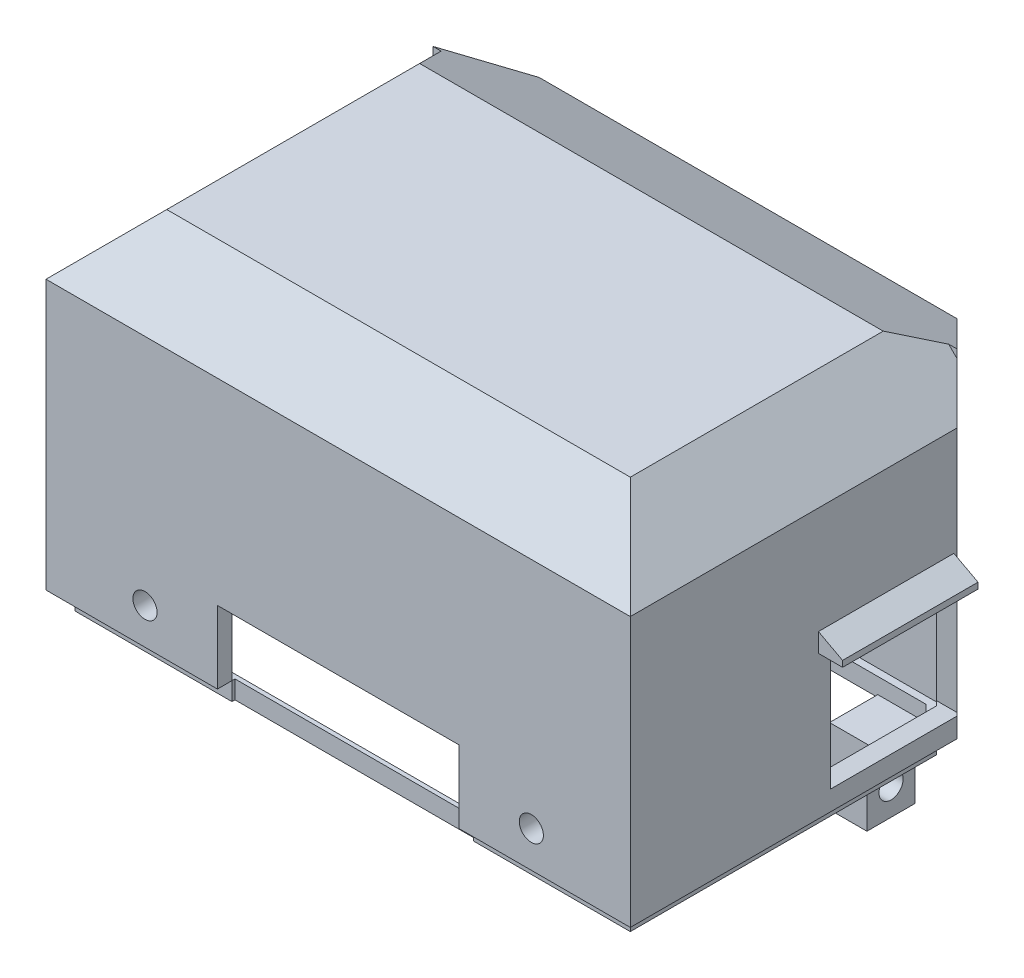
SolidWorks part; units mm, degrees
ref_plane "Front Plane" through (0, 0, 0) normal (0, 0, 1) x (1, 0, 0)
ref_plane "Top Plane" through (0, 0, 0) normal (0, 1, 0) x (1, 0, 0)
ref_plane "Right Plane" through (0, 0, 0) normal (1, 0, 0) x (0, 0, -1)
ref_plane "PXm48_4" through (-48.4, 0, 0) normal (1, 0, 0) x (0, 0, -1)
sketch "Sketch1" plane through (-48.4, 0, 0) normal (1, 0, 0) x (0, 0, -1)
  line L0 (-11.9, -4) -> (48.2, -4)
  line L1 (48.2, -4) -> (48.2, 46.4488)
  line L2 (48.2, 46.4488) -> (40, 50.6)
  line L3 (40, 50.6) -> (-1.9, 50.6)
  line L4 (-1.9, 50.6) -> (-11.9, 40.6)
  line L5 (-11.9, 40.6) -> (-11.9, -4)
extrude "Head Block" add sketch "Sketch1" along normal blind 96.8
sketch "Sketch2" plane through (0, 0, 0) normal (0, 0, 1) x (1, 0, 0)
  line L0 (-37.4, 51.6) -> (-49.4, 51.6)
  line L1 (-49.4, 51.6) -> (-49.4, 39.6)
  line L2 (-49.4, 39.6) -> (-37.4, 51.6)
extrude "Roof Corner Facet L" cut sketch "Sketch2" against normal through all and the other way through all
sketch "Sketch3" plane through (0, 0, 0) normal (0, 0, 1) x (1, 0, 0)
  line L0 (37.4, 51.6) -> (49.4, 51.6)
  line L1 (49.4, 51.6) -> (49.4, 39.6)
  line L2 (49.4, 39.6) -> (37.4, 51.6)
extrude "Roof Corner Facet R" cut sketch "Sketch3" against normal through all and the other way through all
sketch "Sketch4" plane through (0, 0, 0) normal (0, 1, 0) x (1, 0, 0)
  line L0 (-30.4, 60.2) -> (-49.4, 60.2)
  line L1 (-49.4, 60.2) -> (-49.4, 41.2)
  line L2 (-49.4, 41.2) -> (-30.4, 60.2)
extrude "Front Corner Facet L" cut sketch "Sketch4" against normal through all and the other way through all
sketch "Sketch5" plane through (0, 0, 0) normal (0, 1, 0) x (1, 0, 0)
  line L0 (30.4, 60.2) -> (49.4, 60.2)
  line L1 (49.4, 60.2) -> (49.4, 41.2)
  line L2 (49.4, 41.2) -> (30.4, 60.2)
extrude "Front Corner Facet R" cut sketch "Sketch5" against normal through all and the other way through all
shell "Shell" thickness 2.4
ref_plane "PXm47_9" through (-47.9, 0, 0) normal (1, 0, 0) x (0, 0, -1)
sketch "Sketch6" plane through (-47.9, 0, 0) normal (1, 0, 0) x (0, 0, -1)
  line L0 (47.2, 40) -> (56, 40)
  line L1 (56, 40) -> (56, 42.5)
  line L2 (56, 42.5) -> (47.2, 46.955)
  line L3 (47.2, 46.955) -> (47.2, 40)
extrude "Brow" add sketch "Sketch6" along normal blind 95.8
sketch "Sketch7" plane through (0, 0, 0) normal (0, 1, 0) x (1, 0, 0)
  line L0 (-30.4, 60.2) -> (-49.4, 60.2)
  line L1 (-49.4, 60.2) -> (-49.4, 41.2)
  line L2 (-49.4, 41.2) -> (-30.4, 60.2)
extrude "Brow Corner Facet L" cut sketch "Sketch7" against normal through all and the other way through all
sketch "Sketch8" plane through (0, 0, 0) normal (0, 1, 0) x (1, 0, 0)
  line L0 (30.4, 60.2) -> (49.4, 60.2)
  line L1 (49.4, 60.2) -> (49.4, 41.2)
  line L2 (49.4, 41.2) -> (30.4, 60.2)
extrude "Brow Corner Facet R" cut sketch "Sketch8" against normal through all and the other way through all
ref_plane "PYm54_5" through (0, 0, -54.5) normal (0, 0, 1) x (1, 0, 0)
sketch "Sketch9" plane through (0, 0, -54.5) normal (0, 0, 1) x (1, 0, 0)
  line L0 (-46.4, 39.99) -> (46.4, 39.99)
  line L1 (46.4, 39.99) -> (46.4, 40.8)
  line L2 (46.4, 40.8) -> (-46.4, 40.8)
  line L3 (-46.4, 40.8) -> (-46.4, 39.99)
extrude "Brow Drip Groove" cut sketch "Sketch9" along normal blind 1
ref_plane "PZm7" through (0, -7, 0) normal (0, 1, 0) x (1, 0, 0)
sketch "Sketch10" plane through (0, -7, 0) normal (0, 1, 0) x (1, 0, 0)
  line L0 (-46, -9.5) -> (46, -9.5)
  line L1 (46, -9.5) -> (46, 41.2059)
  line L2 (46, 41.2059) -> (41.4059, 45.8)
  line L3 (41.4059, 45.8) -> (-41.4059, 45.8)
  line L4 (-41.4059, 45.8) -> (-46, 41.2059)
  line L5 (-46, 41.2059) -> (-46, -9.5)
  line L6 (-44.8, -8.3) -> (44.8, -8.3)
  line L7 (44.8, -8.3) -> (44.8, 40.7088)
  line L8 (44.8, 40.7088) -> (40.9088, 44.6)
  line L9 (40.9088, 44.6) -> (-40.9088, 44.6)
  line L10 (-40.9088, 44.6) -> (-44.8, 40.7088)
  line L11 (-44.8, 40.7088) -> (-44.8, -8.3)
extrude "Seam Skirt" add sketch "Sketch10" along normal blind 3.01
ref_plane "PZm12_5" through (0, -12.5, 0) normal (0, 1, 0) x (1, 0, 0)
sketch "Sketch11" plane through (0, -12.5, 0) normal (0, 1, 0) x (1, 0, 0)
  line L0 (-45.7, 30) -> (-39.5, 30)
  line L1 (-39.5, 30) -> (-39.5, 38)
  line L2 (-39.5, 38) -> (-45.7, 38)
  line L3 (-45.7, 38) -> (-45.7, 30)
extrude "Seam Block L" add sketch "Sketch11" along normal blind 8.5
ref_plane "PZm4_01" through (0, -4.01, 0) normal (0, 1, 0) x (1, 0, 0)
sketch "Sketch12" plane through (0, -4.01, 0) normal (0, 1, 0) x (1, 0, 0)
  line L0 (-46.2, 30) -> (-39.5, 30)
  line L1 (-39.5, 30) -> (-39.5, 38)
  line L2 (-39.5, 38) -> (-46.2, 38)
  line L3 (-46.2, 38) -> (-46.2, 30)
extrude "Seam Block Root L" add sketch "Sketch12" along normal blind 4.01
ref_plane "PXm45_8" through (-45.8, 0, 0) normal (1, 0, 0) x (0, 0, -1)
sketch "Sketch13" plane through (-45.8, 0, 0) normal (1, 0, 0) x (0, 0, -1)
  circle A0 centre (34, -8) radius 2
extrude "Seam Insert L" cut sketch "Sketch13" along normal blind 6.1
sketch "Sketch14" plane through (0, -12.5, 0) normal (0, 1, 0) x (1, 0, 0)
  line L0 (39.5, 30) -> (45.7, 30)
  line L1 (45.7, 30) -> (45.7, 38)
  line L2 (45.7, 38) -> (39.5, 38)
  line L3 (39.5, 38) -> (39.5, 30)
extrude "Seam Block R" add sketch "Sketch14" along normal blind 8.5
sketch "Sketch15" plane through (0, -4.01, 0) normal (0, 1, 0) x (1, 0, 0)
  line L0 (39.5, 30) -> (46.2, 30)
  line L1 (46.2, 30) -> (46.2, 38)
  line L2 (46.2, 38) -> (39.5, 38)
  line L3 (39.5, 38) -> (39.5, 30)
extrude "Seam Block Root R" add sketch "Sketch15" along normal blind 4.01
ref_plane "PX39_7" through (39.7, 0, 0) normal (1, 0, 0) x (0, 0, -1)
sketch "Sketch16" plane through (39.7, 0, 0) normal (1, 0, 0) x (0, 0, -1)
  circle A0 centre (34, -8) radius 2
extrude "Seam Insert R" cut sketch "Sketch16" along normal blind 6.1
ref_plane "PY9" through (0, 0, 9) normal (0, 0, 1) x (1, 0, 0)
sketch "Sketch17" plane through (0, 0, 9) normal (0, 0, 1) x (1, 0, 0)
  line L0 (-20, -8) -> (20, -8)
  line L1 (20, -8) -> (20, 8)
  line L2 (20, 8) -> (-20, 8)
  line L3 (-20, 8) -> (-20, -8)
extrude "Cable Window" cut sketch "Sketch17" along normal blind 3.9
ref_plane "PY3_5" through (0, 0, 3.5) normal (0, 0, 1) x (1, 0, 0)
sketch "Sketch18" plane through (0, 0, 3.5) normal (0, 0, 1) x (1, 0, 0)
  circle A0 centre (-32, 2) radius 4
  circle A1 centre (32, 2) radius 4
extrude "Flange Bosses" add sketch "Sketch18" along normal blind 6.2
ref_plane "PY5_4" through (0, 0, 5.4) normal (0, 0, 1) x (1, 0, 0)
sketch "Sketch19" plane through (0, 0, 5.4) normal (0, 0, 1) x (1, 0, 0)
  circle A0 centre (-32, 2) radius 2
  circle A1 centre (32, 2) radius 2
extrude "Flange Insert Holes" cut sketch "Sketch19" along normal blind 7
ref_plane "PZ17" through (0, 17, 0) normal (0, 1, 0) x (1, 0, 0)
sketch "Sketch20" plane through (0, 17, 0) normal (0, 1, 0) x (1, 0, 0)
  line L0 (-18.9, 29.3) -> (-14.9, 29.3)
  line L1 (-14.9, 29.3) -> (-14.9, 46.3)
  line L2 (-14.9, 46.3) -> (-18.9, 46.3)
  line L3 (-18.9, 46.3) -> (-18.9, 29.3)
extrude "Camera Rail L" add sketch "Sketch20" along normal blind 29
sketch "Sketch21" plane through (0, 17, 0) normal (0, 1, 0) x (1, 0, 0)
  line L0 (-15.4, 29.3) -> (-12.9, 29.3)
  line L1 (-12.9, 29.3) -> (-12.9, 30.35)
  line L2 (-12.9, 30.35) -> (-15.4, 30.35)
  line L3 (-15.4, 30.35) -> (-15.4, 29.3)
extrude "Camera Rear Lip L" add sketch "Sketch21" along normal blind 27.2
sketch "Sketch22" plane through (0, 17, 0) normal (0, 1, 0) x (1, 0, 0)
  line L0 (14.9, 29.3) -> (18.9, 29.3)
  line L1 (18.9, 29.3) -> (18.9, 46.3)
  line L2 (18.9, 46.3) -> (14.9, 46.3)
  line L3 (14.9, 46.3) -> (14.9, 29.3)
extrude "Camera Rail R" add sketch "Sketch22" along normal blind 29
sketch "Sketch23" plane through (0, 17, 0) normal (0, 1, 0) x (1, 0, 0)
  line L0 (12.9, 29.3) -> (15.4, 29.3)
  line L1 (15.4, 29.3) -> (15.4, 30.35)
  line L2 (15.4, 30.35) -> (12.9, 30.35)
  line L3 (12.9, 30.35) -> (12.9, 29.3)
extrude "Camera Rear Lip R" add sketch "Sketch23" along normal blind 27.2
ref_plane "PZ45_5" through (0, 45.5, 0) normal (0, 1, 0) x (1, 0, 0)
sketch "Sketch24" plane through (0, 45.5, 0) normal (0, 1, 0) x (1, 0, 0)
  line L0 (-18.9, 34) -> (18.9, 34)
  line L1 (18.9, 34) -> (18.9, 38)
  line L2 (18.9, 38) -> (-18.9, 38)
  line L3 (-18.9, 38) -> (-18.9, 34)
extrude "Camera Top Bar" add sketch "Sketch24" along normal blind 1.5
ref_plane "PZ16_5" through (0, 16.5, 0) normal (0, 1, 0) x (1, 0, 0)
sketch "Sketch25" plane through (0, 16.5, 0) normal (0, 1, 0) x (1, 0, 0)
  circle A0 centre (-16.9, 31) radius 0.8
  circle A1 centre (-16.9, 43.5) radius 0.8
  circle A2 centre (16.9, 31) radius 0.8
  circle A3 centre (16.9, 43.5) radius 0.8
extrude "Retainer Pilots" cut sketch "Sketch25" along normal blind 7.5
sketch "Sketch26" plane through (0, 0, 0) normal (0, 1, 0) x (1, 0, 0)
  line L0 (0, 33) -> (0, 43)
ref_plane "Plane15" through (0, 0, -43) normal (0, 0, -1) x (-1, 0, 0)
sketch "Sketch28" plane through (0, 0, -43) normal (0, 0, -1) x (-1, 0, 0)
  line L0 (4.8, 23.8) -> (-4.8, 23.8)
  line L1 (-4.8, 23.8) -> (-4.8, 33.4)
  line L2 (-4.8, 33.4) -> (4.8, 33.4)
  line L3 (4.8, 33.4) -> (4.8, 23.8)
extrude "Camera Window" cut sketch "Sketch28" along normal blind 6.7 draft 29.75 draft outward yes
sketch "Sketch29" plane through (0, 0, 0) normal (0, 1, 0) x (1, 0, 0)
  line L0 (-14.5, 32) -> (-24.5, 32)
ref_plane "Plane16" through (-24.5, 0, -32) normal (-1, 0, 0) x (0, 0, 1)
sketch "Sketch31" plane through (-24.5, 0, -32) normal (-1, 0, 0) x (0, 0, 1)
  line L0 (3.2, 6.8) -> (-3.2, 6.8)
  line L1 (-3.2, 6.8) -> (-3.2, 11.2)
  line L2 (-3.2, 11.2) -> (3.2, 11.2)
  line L3 (3.2, 11.2) -> (3.2, 6.8)
extrude "ToF Window Left" cut sketch "Sketch31" along normal blind 25.4 draft 17.5
sketch "Sketch32" plane through (0, 0, 0) normal (0, 1, 0) x (1, 0, 0)
  line L0 (0, 33) -> (0, 43)
ref_plane "Plane17" through (0, 0, -43) normal (0, 0, -1) x (-1, 0, 0)
sketch "Sketch34" plane through (0, 0, -43) normal (0, 0, -1) x (-1, 0, 0)
  line L0 (3.2, 6.8) -> (-3.2, 6.8)
  line L1 (-3.2, 6.8) -> (-3.2, 11.2)
  line L2 (-3.2, 11.2) -> (3.2, 11.2)
  line L3 (3.2, 11.2) -> (3.2, 6.8)
extrude "ToF Window Ahead" cut sketch "Sketch34" along normal blind 6.7 draft 17.5 draft outward yes
sketch "Sketch35" plane through (0, 0, 0) normal (0, 1, 0) x (1, 0, 0)
  line L0 (14.5, 32) -> (24.5, 32)
ref_plane "Plane18" through (24.5, 0, -32) normal (1, 0, 0) x (0, 0, -1)
sketch "Sketch37" plane through (24.5, 0, -32) normal (1, 0, 0) x (0, 0, -1)
  line L0 (3.2, 6.8) -> (-3.2, 6.8)
  line L1 (-3.2, 6.8) -> (-3.2, 11.2)
  line L2 (-3.2, 11.2) -> (3.2, 11.2)
  line L3 (3.2, 11.2) -> (3.2, 6.8)
extrude "ToF Window Right" cut sketch "Sketch37" along normal blind 25.4 draft 17.5
ref_plane "PXm13" through (-13, 0, 0) normal (1, 0, 0) x (0, 0, -1)
sketch "Sketch38" plane through (-13, 0, 0) normal (1, 0, 0) x (0, 0, -1)
  line L0 (47.7, 14) -> (54.2, 14)
  line L1 (54.2, 14) -> (54.2, 15)
  line L2 (54.2, 15) -> (47.7, 18.6)
  line L3 (47.7, 18.6) -> (47.7, 14)
extrude "ToF Hood Ahead" add sketch "Sketch38" along normal blind 26
ref_plane "PYm41_7" through (0, 0, -41.7) normal (0, 0, 1) x (1, 0, 0)
sketch "Sketch39" plane through (0, 0, -41.7) normal (0, 0, 1) x (1, 0, 0)
  line L0 (-47.9, 19.7356) -> (-52.4, 19.7356)
  line L1 (-52.4, 19.7356) -> (-52.4, 20.7356)
  line L2 (-52.4, 20.7356) -> (-47.9, 23.1356)
  line L3 (-47.9, 23.1356) -> (-47.9, 19.7356)
extrude "ToF Hood Left" add sketch "Sketch39" along normal blind 22.4356
sketch "Sketch40" plane through (0, 0, -41.7) normal (0, 0, 1) x (1, 0, 0)
  line L0 (47.9, 19.7356) -> (52.4, 19.7356)
  line L1 (52.4, 19.7356) -> (52.4, 20.7356)
  line L2 (52.4, 20.7356) -> (47.9, 23.1356)
  line L3 (47.9, 23.1356) -> (47.9, 19.7356)
extrude "ToF Hood Right" add sketch "Sketch40" along normal blind 22.4356
ref_plane "PYm49_2" through (0, 0, -49.2) normal (0, 0, 1) x (1, 0, 0)
sketch "Sketch41" plane through (0, 0, -49.2) normal (0, 0, 1) x (1, 0, 0)
  line L0 (-49.4, 1.5) -> (49.4, 1.5)
  line L1 (49.4, 1.5) -> (49.4, 3.5)
  line L2 (49.4, 3.5) -> (-49.4, 3.5)
  line L3 (-49.4, 3.5) -> (-49.4, 1.5)
extrude "Light-Bar Groove" cut sketch "Sketch41" along normal blind 2
ref_plane "PY5_5" through (0, 0, 5.5) normal (0, 0, 1) x (1, 0, 0)
sketch "Sketch42" plane through (0, 0, 5.5) normal (0, 0, 1) x (1, 0, 0)
  line L0 (-8, 11) -> (8, 11)
  line L1 (8, 11) -> (8, 17)
  line L2 (8, 17) -> (-8, 17)
  line L3 (-8, 17) -> (-8, 11)
extrude "Ribbon Tie Anchor" add sketch "Sketch42" along normal blind 4.2
ref_plane "PXm9" through (-9, 0, 0) normal (1, 0, 0) x (0, 0, -1)
sketch "Sketch43" plane through (-9, 0, 0) normal (1, 0, 0) x (0, 0, -1)
  line L0 (-9, 12) -> (-7, 12)
  line L1 (-7, 12) -> (-7, 16)
  line L2 (-7, 16) -> (-9, 16)
  line L3 (-9, 16) -> (-9, 12)
extrude "Ribbon Tie Slot" cut sketch "Sketch43" along normal blind 18
equation "\"BOARD_REAR\" = 86.0"
equation "\"BOARD_FRONT\" = 41.0"
equation "\"BOARD_END\" = 22.0"
equation "\"BOARD_ANGLED\" = 30.0"
equation "\"BOARD_DEPTH\" = 41.8431"
equation "\"PCB_T\" = 1.6"
equation "\"ABOVE_PCB\" = 14.0"
equation "\"BELOW_PCB\" = 6.0"
equation "\"MID_PARTS_H\" = 9.0"
equation "\"BOARD_HOLE_PILOT\" = 1.6"
equation "\"J2_X\" = 19.0"
equation "\"DUPONT_DROP\" = 14.0"
equation "\"BEND_R\" = 5.0"
equation "\"BOARD_GAP\" = 3.0"
equation "\"TOF_FOV\" = 25.0"
equation "\"TOF_MARGIN_DEG\" = 5.0"
equation "\"TOF_WIN_MARGIN\" = 1.0"
equation "\"TOF_Z\" = 9.0"
equation "\"TOF_SIDE_BEARING\" = 90.0"
equation "\"TOF_CONE_LEN\" = 70.0"
equation "\"CAM_W\" = 29.2"
equation "\"CAM_H\" = 28.2"
equation "\"CAM_D\" = 12.35"
equation "\"CAM_FRONT_Y\" = 43.0"
equation "\"CAM_BOTTOM_Z\" = 17.0"
equation "\"CAM_LENS_UP\" = 11.6"
equation "\"CAM_LENS_OPEN\" = 9.6"
equation "\"CAM_HFOV\" = 53.5"
equation "\"CAM_VFOV\" = 41.41"
equation "\"CAM_FOV_MARGIN\" = 3.0"
equation "\"CAM_FIT\" = 0.3"
equation "\"RIBBON_W\" = 16.0"
equation "\"RIBBON_T\" = 0.3"
equation "\"RIBBON_LEN\" = 150.0"
equation "\"RIBBON_EXIT_Y\" = 35.0"
equation "\"WALL\" = 2.4"
equation "\"HEAD_X\" = 48.4"
equation "\"HEAD_REAR_Y\" = -11.9"
equation "\"CAM_FOAM\" = 2.8"
equation "\"HEAD_FRONT_Y\" = 48.2"
equation "\"HEAD_TOP_Z\" = 50.6"
equation "\"HEAD_BOT_Z\" = -28.4"
equation "\"HEAD_SPLIT_Z\" = -4.0"
equation "\"SKIRT_T\" = 1.2"
equation "\"SKIRT_H\" = 3.0"
equation "\"SKIRT_FIT\" = 0.3"
equation "\"VISOR\" = 7.8"
equation "\"VISOR_Z\" = 40.0"
equation "\"ROOF_SLOPE_Y\" = 40.0"
equation "\"ROOF_CHAMFER\" = 10.0"
equation "\"REAR_CHAMFER\" = 10.0"
equation "\"CORNER_CHAMFER\" = 6.0"
equation "\"LOWER_SIDE_FACET\" = 6.0"
equation "\"LIGHTBAR_DEPTH\" = 1.0"
equation "\"HOOD_Z\" = 14.0"
equation "\"HOOD_L\" = 6.0"
equation "\"SIDE_HOOD_L\" = 4.0"
equation "\"INSERT_M3_D\" = 4.0"
equation "\"INSERT_M3_L\" = 6.0"
equation "\"M3_CLEAR\" = 3.4"
equation "\"M2_PILOT\" = 1.6"
equation "\"M25_PILOT\" = 2.2"
equation "\"BOX_X\" = 72.4"
equation "\"BOX_FRONT_Y\" = -11.9"
equation "\"BOX_REAR_Y\" = -124.4"
equation "\"BOX_BOT_Z\" = -28.4"
equation "\"BOX_TOP_Z\" = 26.0"
equation "\"LID_T\" = 2.4"
equation "\"LID_SKIRT\" = 1.6"
equation "\"LID_TONGUE_H\" = 3.0"
equation "\"LID_FIT\" = 0.3"
equation "\"PI_STANDOFF\" = 8.0"
equation "\"BOX_REAR_CHAMFER\" = 8.0"
equation "\"BOX_REAR_FACET\" = 4.0"
equation "\"VENT_UPSTAND\" = 3.0"
equation "\"TUBE_D\" = 22.2"
equation "\"TUBE_LINER\" = 1.0"
equation "\"MOUNT_Y\" = -70.0"
equation "\"RAIL_W\" = 30.0"
equation "\"RAIL_W2\" = 38.0"
equation "\"RAIL_H\" = 6.0"
equation "\"SLIDE\" = 0.3"
equation "\"STOP_T\" = 6.0"
equation "\"CLAMP_W\" = 40.0"
equation "\"CLAMP_HALF\" = 20.0"
equation "\"CLAMP_DROP\" = 12.0"
equation "\"CAP_T\" = 12.0"
equation "\"CLAMP_BOLT_OFF\" = 16.6"
equation "\"M5_INSERT_D\" = 6.4"
equation "\"M5_CLEAR\" = 5.5"
equation "\"LOCK_D\" = 3.3"
equation "\"POD_TILT_DEG\" = 0.0"
equation "\"PRINT_LIMIT\" = 180.0"
equation "\"PI5_L\" = 85.0"
equation "\"PI5_W\" = 56.0"
equation "\"PI5_T\" = 1.6"
equation "\"PI5_USBC_BX\" = 11.2"
equation "\"PI5_ETH_BY\" = 10.2"
equation "\"PI5_PORT_OVERHANG\" = 3.0"
equation "\"PI5_FPC_H\" = 5.0"
equation "\"PI5_FPC_USE\" = 0.0"
equation "\"PI5_PIN1_BX\" = 8.37"
equation "\"HEADER_BASE_H\" = 2.5"
equation "\"DUPONT_L\" = 14.0"
equation "\"PI5_UNDERSIDE\" = 1.5"
equation "\"COOLER_H\" = 15.0"
equation "\"HAT_W\" = 65.0"
equation "\"HAT_D\" = 56.5"
equation "\"HAT_T\" = 1.6"
equation "\"HAT_SPACER\" = 16.0"
equation "\"HAILO_H\" = 10.0"
equation "\"STACK_PINS_H\" = 6.0"
equation "\"DUPONT_SEAT\" = 0.5"
equation "\"PCIE_FFC_LOOP\" = 6.0"
equation "\"HAILO_AIR_GAP_MIN\" = 8.0"
equation "\"M25_CLEAR\" = 2.7"
equation "\"PI_X0\" = -55.0"
equation "\"PI_Y1\" = -36.5"
equation "\"PI_Y0\" = -92.5"
equation "\"BOX_LEN\" = 112.5"
equation "\"COVER_T\" = 3.0"
equation "\"COVER_TOP_Z\" = 6.5"
equation "\"SIDE_LEDGE_Z\" = -2.5"
equation "\"UPPER_LEDGE_Z\" = 15.5"
equation "\"REAR_LEDGE_Z\" = 8.0"
equation "\"LEDGE_L\" = 4.0"
equation "\"RIBBON_W_PI\" = 11.5"
equation "\"RIBBON_RUN_Z\" = 12.0"
equation "\"RIBBON_SPEC_LEN\" = 200.0"
